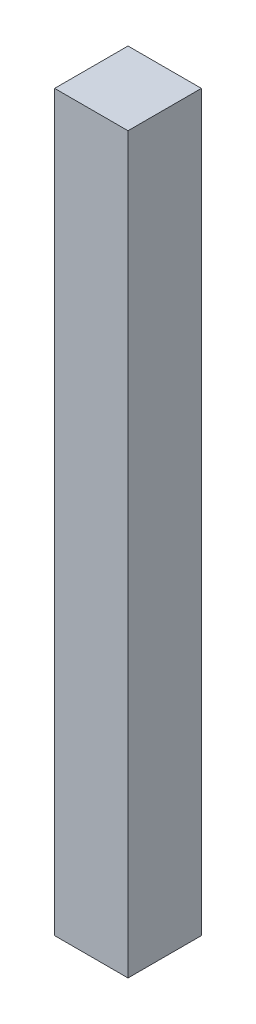
SolidWorks part; units mm, degrees
ref_plane "前基準面" through (0, 0, 0) normal (0, 0, 1) x (1, 0, 0)
ref_plane "上基準面" through (0, 0, 0) normal (0, 1, 0) x (1, 0, 0)
ref_plane "右基準面" through (0, 0, 0) normal (1, 0, 0) x (0, 0, -1)
sketch "草圖1" plane through (0, 0, 0) normal (0, 1, 0) x (1, 0, 0)
  line L1 (-10, 10) -> (10, 10)
  line L2 (-10, 10) -> (-10, -10)
  line L3 (-10, -10) -> (10, -10)
  line L4 (10, 10) -> (10, -10)
  line L5 (0, -10) -> (0, 10) construction
  line L6 (-10, 0) -> (10, 0) construction
  point P0 (0, 0)
  dimension "D1" = 20
  dimension "D2" = 20
extrude "填料-伸長1" add sketch "草圖1" along normal blind 200
